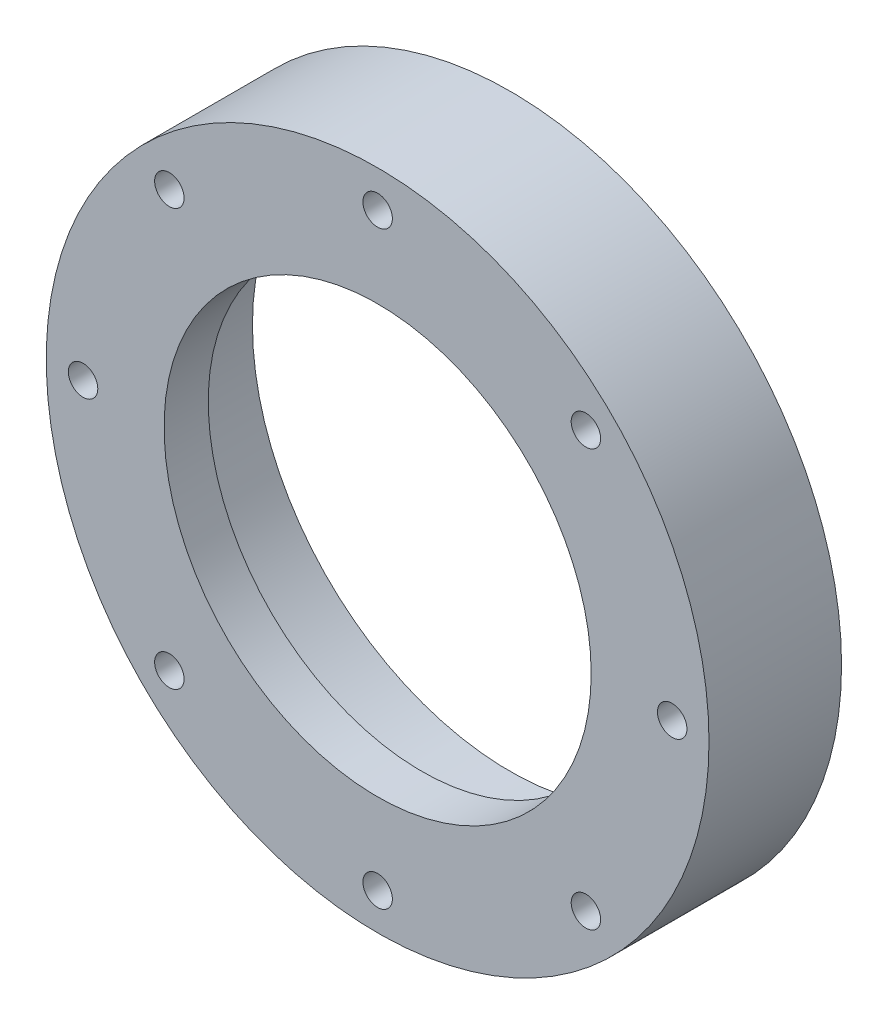
SolidWorks part; units mm, degrees
ref_plane "前视基准面" through (0, 0, 0) normal (0, 0, 1) x (1, 0, 0)
ref_plane "上视基准面" through (0, 0, 0) normal (0, 1, 0) x (1, 0, 0)
ref_plane "右视基准面" through (0, 0, 0) normal (1, 0, 0) x (0, 0, -1)
sketch "草图1" plane through (0, 0, 0) normal (0, 0, 1) x (1, 0, 0)
  circle A0 centre (0, 0) radius 35
  circle A1 centre (0, 0) radius 45
  dimension "D1" = 70
  dimension "D2" = 90
extrude "凸台-拉伸1" add sketch "草图1" along normal blind 12
sketch "草图2" plane through (0, 0, 12) normal (0, 0, 1) x (1, 0, 0)
  circle A0 centre (0, 0) radius 29
  circle A1 centre (0, 0) radius 45 construction
  circle A2 centre (0, 0) radius 45
  dimension "D1" = 58
extrude "凸台-拉伸2" add sketch "草图2" along normal blind 6
sketch "草图4" plane through (0, 0, 18) normal (0, 0, 1) x (1, 0, 0)
  circle A0 centre (0, 40) radius 2
  circle A1 centre (28.2843, 28.2843) radius 2
  circle A2 centre (40, 0) radius 2
  circle A3 centre (28.2843, -28.2843) radius 2
  circle A4 centre (0, -40) radius 2
  circle A5 centre (-28.2843, -28.2843) radius 2
  circle A6 centre (-40, 0) radius 2
  circle A7 centre (-28.2843, 28.2843) radius 2
  point P4 (0, 0)
  point P19 (0, 0)
  dimension "D1" = 4
  dimension "D2" = 40
  dimension "D3" = 8
extrude "切除-拉伸1" cut sketch "草图4" against normal up to vertex (18 mm away) up to point (0, 0, 0)
